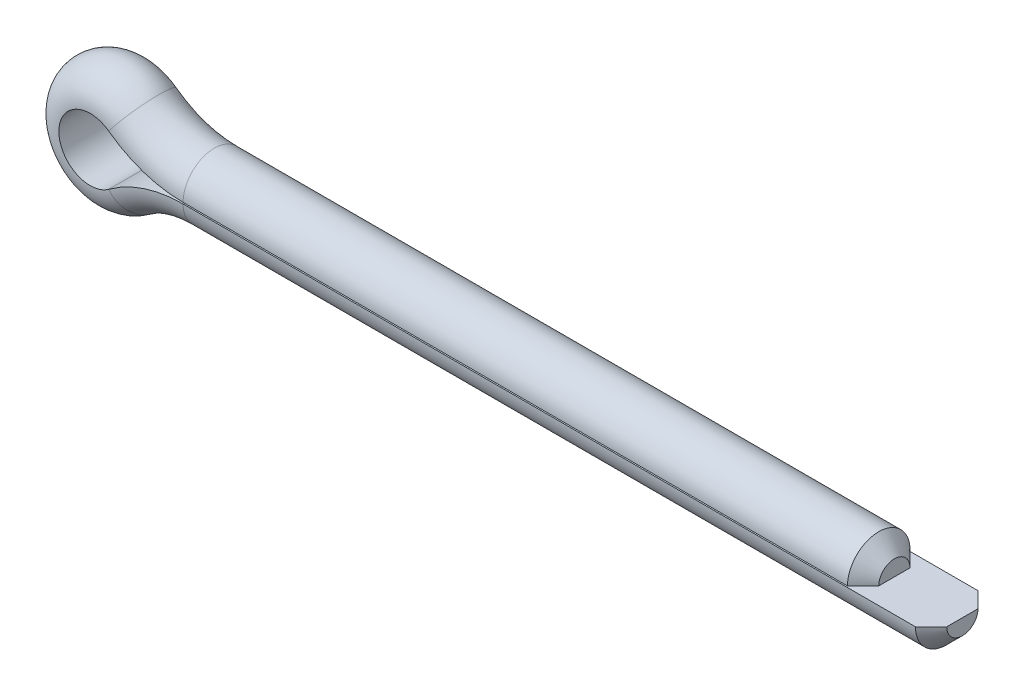
SolidWorks part; units mm, degrees
ref_plane "Front" through (0, 0, 0) normal (0, 0, 1) x (1, 0, 0)
ref_plane "Top" through (0, 0, 0) normal (0, 1, 0) x (1, 0, 0)
ref_plane "Right" through (0, 0, 0) normal (1, 0, 0) x (0, 0, -1)
sketch "Sketch1" plane through (0, 0, 0) normal (0, 0, 1) x (1, 0, 0)
  line L0 (-28.4159, 0) -> (2.5, 0) construction
  line L1 (-25, -0.0254) -> (2.5, -0.0254)
  line L2 (-27.2662, 0.0254) -> (2.5, 0.0254) construction
  line L3 (-25, 0.0254) -> (0, 0.0254)
  line L4 (-11.4985, 0.0254) -> (2.5, 0.0254) construction
  line L5 (-11.4985, -0.0254) -> (2.5, -0.0254) construction
  line L6 (-28.4159, 1.15) -> (-28.4159, 0) construction
  line L7 (-28.4159, 1.15) -> (-28.4159, 2.3) construction
  line L8 (-11.4985, 0) -> (2.5, 0) construction
  line L9 (0, 0.0254) -> (0, 0) construction
  line L10 (-28.4159, 0) -> (-28.4159, -2.3) construction
  arc A1 (-27.7327, 0.9251) -> (-27.7327, -0.9251) centre (-28.4159, 0) ccw
  arc A2 (-25, -0.0254) -> (-27.7327, -0.9251) centre (-25, -4.6254) ccw
  arc A3 (-27.7327, 0.9251) -> (-25, 0.0254) centre (-25, 4.6254) ccw
  circle A4 centre (-28.4159, 0) radius 2.3 construction
  point P15 (0, 0.0254)
  dimension "D6" = 4.6
  dimension "D4" = 0.0254
  dimension "D5" = 0.0254
sketch "Sketch2" plane through (0, 0, 0) normal (1, 0, 0) x (0, 0, -1)
  line L0 (-1.15, 0.0254) -> (1.15, 0.0254)
  arc A0 (1.15, 0.0254) -> (-1.15, 0.0254) centre (0, 0.0254) ccw
sweep "Sweep1" add profiles "Sketch2" path "Sketch1"
chamfer "Chamfer1" distance 0.575 angle 45 2 edges at (2.5, -1.1754, 0) (0, 1.1754, 0)
equation "\"D6@Sketch1\" = \"HeadOD@Sketch1\""
equation "\"WireWidth@Sketch2\" = \"WireWidth@Sketch1\""
equation "\"D1@Chamfer1\" = \"WireWidth@Sketch1\"*.25"
